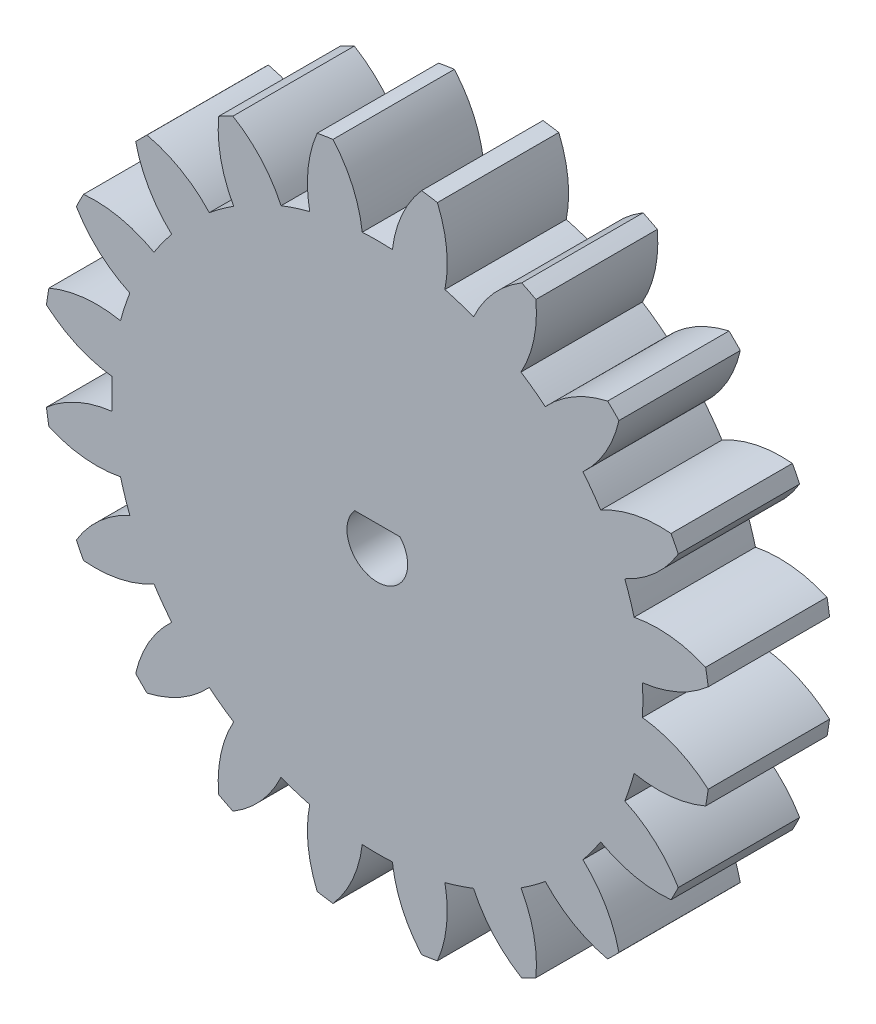
SolidWorks part; units mm, degrees
material "Barra Redonda SAE 1020 - 2\""
ref_plane "Plano frontal" through (0, 0, 0) normal (0, 0, 1) x (1, 0, 0)
ref_plane "Plano superior" through (0, 0, 0) normal (0, 1, 0) x (1, 0, 0)
ref_plane "Plano direito" through (0, 0, 0) normal (1, 0, 0) x (0, 0, -1)
sketch "Esboço1" plane through (0, 0, 0) normal (0, 1, 0) x (1, 0, 0)
  line L0 (0, 0) -> (0, -42.215) construction
  line L1 (0, 0) -> (33, 0)
  line L2 (0, 0) -> (0, 12)
  line L3 (0, 12) -> (33, 12)
  line L4 (33, 0) -> (33, 12)
  dimension "D1" = 12
  dimension "D2" = 66
revolve "Revolução1" add sketch "Esboço1" angle 360 about L0
sketch "Esboço2" plane through (0, 0, 0) normal (0, 0, 1) x (1, 0, 0)
  line L0 (0, 0) -> (0, 86.3394) construction
  line L1 (0, 0) -> (-2.5409, 29.8922) construction
  line L2 (0, 0) -> (-9.3616, 59.1066) construction
  line L3 (-2.5409, 29.8922) -> (-4.6808, 29.5533) construction
  arc A0 (1.4893, 26.2067) -> (-1.4893, 26.2067) centre (0, 0) ccw
  arc A1 (4.4016, 32.7308) -> (-4.4016, 32.7308) centre (0, 0) ccw
  circle A2 centre (0, 0) radius 30 construction
  circle A3 centre (0, 0) radius 28.1908 construction
  arc A4 (-1.4893, 26.2067) -> (-4.4016, 32.7308) centre (-13.4064, 24.799) ccw
  arc A5 (4.4016, 32.7308) -> (1.4893, 26.2067) centre (13.4064, 24.799) ccw
  dimension "D1" = 52.498
  dimension "D2" = 66.0508
  dimension "D3" = 60
  dimension "D6" = 56.3816
  dimension "D7" = 12
  dimension "D4" = 9
  dimension "D5" = 2.1665
sketch "Esboço3" plane through (0, 0, -12) normal (0, 0, -1) x (-1, 0, 0)
  line L0 (-2.2361, 2) -> (2.2361, 2)
  arc A0 (-2.2361, 2) -> (2.2361, 2) centre (0, 0) ccw
  dimension "D1" = 6
  dimension "D2" = 2
extrude "Corte-extrusão2" cut sketch "Esboço3" against normal through all contours L0 A0
extrude "Corte-extrusão3" cut sketch "Esboço2" against normal through all
pattern_circular "PadrãoCircular2" count 20 over 360 about axis through (0, 0, 0) along (0, 0, 1) of "Corte-extrusão3"
